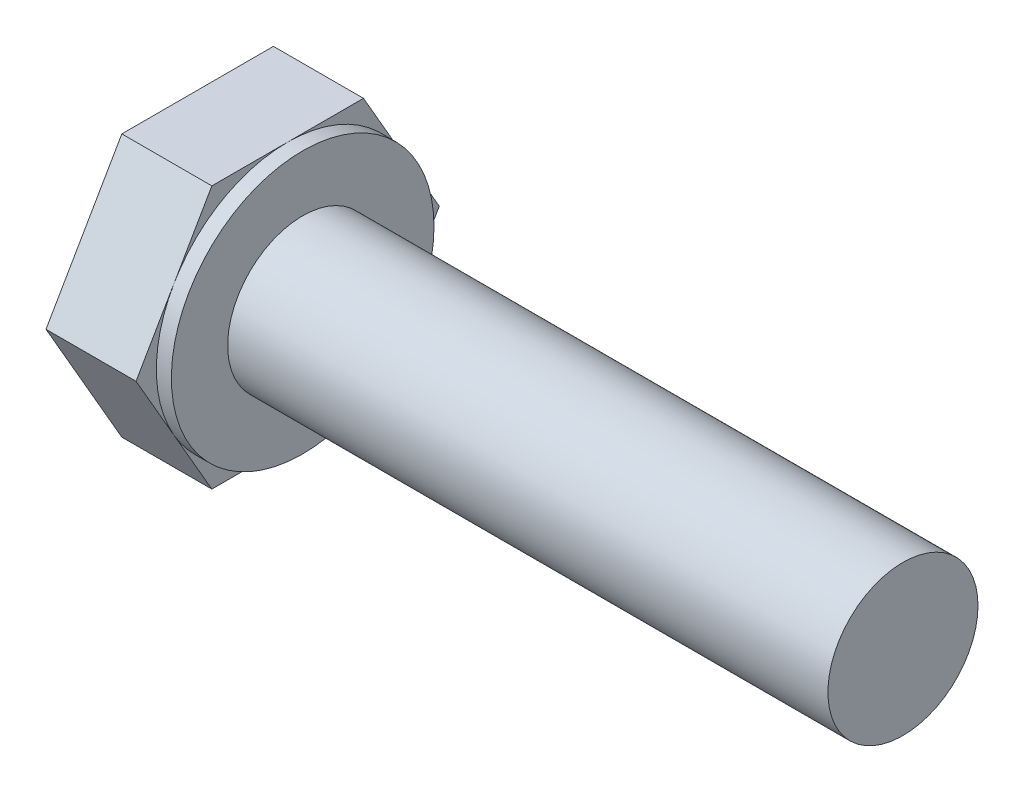
SolidWorks part; units mm, degrees
material "Plain Carbon Steel"
ref_plane "Front Plane" through (0, 0, 0) normal (0, 0, 1) x (1, 0, 0)
ref_plane "Top Plane" through (0, 0, 0) normal (0, 1, 0) x (1, 0, 0)
ref_plane "Right Plane" through (0, 0, 0) normal (1, 0, 0) x (0, 0, -1)
sketch "Sketch1" plane through (0, 0, 0) normal (1, 0, 0) x (0, 0, -1)
  line L1 (-4.0415, 0) -> (-2.0207, -3.5)
  line L2 (-2.0207, -3.5) -> (2.0207, -3.5)
  line L3 (2.0207, -3.5) -> (4.0415, 0)
  line L4 (4.0415, 0) -> (2.0207, 3.5)
  line L5 (2.0207, 3.5) -> (-2.0207, 3.5)
  line L6 (-2.0207, 3.5) -> (-4.0415, 0)
  circle A0 centre (0, 0) radius 3.5 construction
  dimension "D1" = 7
extrude "Boss-Extrude1" add sketch "Sketch1" against normal blind 2.4
sketch "Sketch2" plane through (0, 0, 0) normal (1, 0, 0) x (0, 0, -1)
  line L0 (2.0207, 3.5) -> (-2.0207, 3.5) construction
  circle A0 centre (0, 0) radius 3.5
extrude "Boss-Extrude2" add sketch "Sketch2" along normal blind 0.4
sketch "Sketch3" plane through (0.4, 0, 0) normal (1, 0, 0) x (0, 0, -1)
  circle A0 centre (0, 0) radius 2
  dimension "D1" = 4
extrude "Boss-Extrude3" add sketch "Sketch3" along normal blind 16
